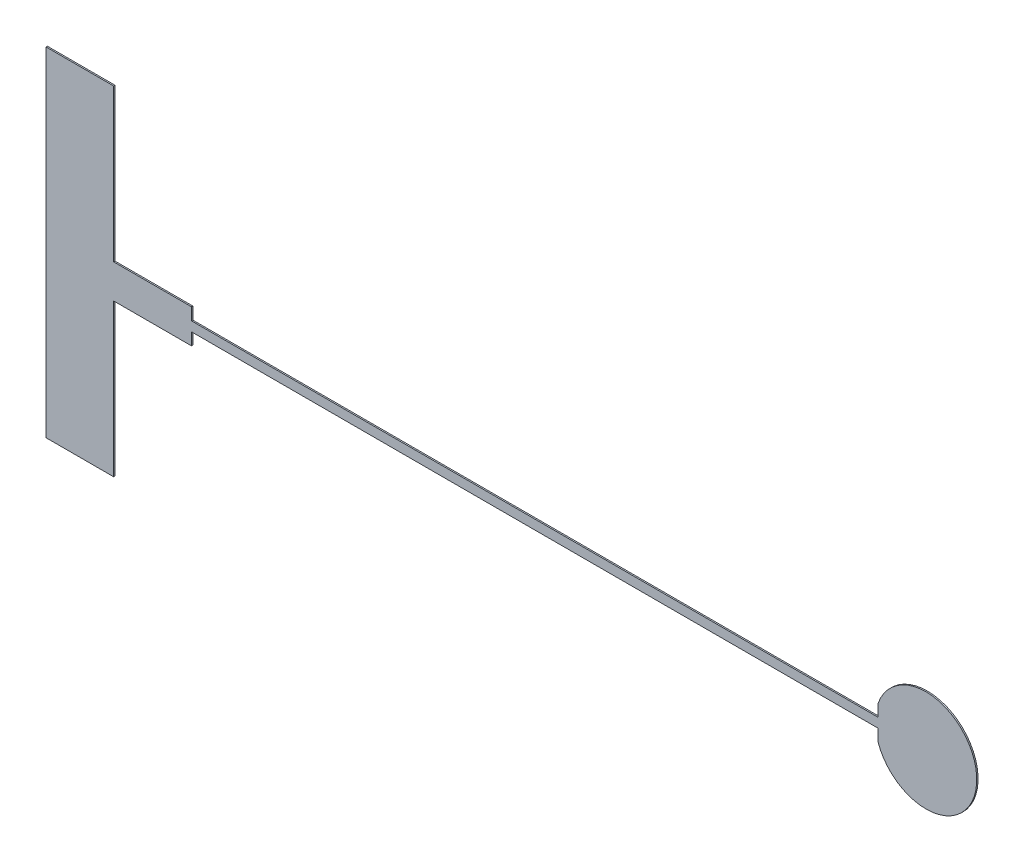
SolidWorks part; units mm, degrees
ref_plane "Front Plane" through (0, 0, 0) normal (0, 0, 1) x (1, 0, 0)
ref_plane "Top Plane" through (0, 0, 0) normal (0, 1, 0) x (1, 0, 0)
ref_plane "Right Plane" through (0, 0, 0) normal (1, 0, 0) x (0, 0, -1)
sketch "Sketch1" plane through (0, 0, 0) normal (0, 0, 1) x (1, 0, 0)
  line L0 (1000, 250) -> (5000, 250)
  line L1 (-1000, 2500) -> (1000, 2500)
  line L2 (-1000, 2500) -> (-1000, -2500)
  line L3 (-1000, -2500) -> (1000, -2500)
  line L4 (1000, 2500) -> (1000, 250)
  line L5 (-1000, 2500) -> (1000, -2500) construction
  line L6 (-1000, -2500) -> (1000, 2500) construction
  line L9 (1000, -250) -> (5000, -250)
  line L10 (5000, 250) -> (5000, 125)
  line L11 (-3000, 250) -> (5000, -250) construction
  line L12 (-3000, -250) -> (5000, 250) construction
  line L13 (5000, 125) -> (9000, 125)
  line L15 (5000, -125) -> (9000, -125)
  line L16 (9000, 125) -> (9000, 100)
  line L17 (1000, 125) -> (9000, -125) construction
  line L18 (1000, -125) -> (9000, 125) construction
  line L19 (9000, 100) -> (11256.6966, 100)
  line L21 (9000, -100) -> (11256.6966, -100)
  line L23 (6000, 100) -> (12000, -100) construction
  line L24 (6000, -100) -> (12000, 100) construction
  line L25 (1000, -250) -> (1000, -2500)
  line L26 (5000, -125) -> (5000, -250)
  line L27 (9000, -100) -> (9000, -125)
  arc A0 (11256.6966, -100) -> (11256.6966, 100) centre (12000, 0) ccw
  point P0 (0, 0)
  point P6 (1000, 0)
  point P11 (5000, 0)
  point P16 (9000, 0)
  dimension "D9" = 1500
  dimension "D1" = 2000
  dimension "D2" = 5000
  dimension "D3" = 500
  dimension "D4" = 4000
  dimension "D5" = 250
  dimension "D6" = 4000
  dimension "D7" = 200
extrude "Boss-Extrude1" add sketch "Sketch1" against normal blind 20
sketch "Sketch2" plane through (0, 0, 0) normal (0, 0, 1) x (1, 0, 0)
  line L0 (0, -11) -> (0, 11) construction
  line L1 (1000, 2500) -> (0, 2500)
  line L2 (1000, 2500) -> (1000, 250)
  line L3 (1000, 250) -> (0, 250)
  line L4 (0, 2500) -> (0, 250)
  line L5 (1000, -2500) -> (0, -2500)
  line L6 (1000, -2500) -> (1000, -250)
  line L7 (1000, -250) -> (0, -250)
  line L8 (0, -2500) -> (0, -250)
  dimension "D1" = 1000
  dimension "D2" = 2250
extrude "Cut-Extrude1" cut sketch "Sketch2" against normal through all
sketch "Sketch3" plane through (0, 0, 0) normal (0, 0, 1) x (1, 0, 0)
  line L0 (0, 0) -> (1098.3807, 0) construction
  line L1 (11, 0) -> (-11, 0) construction
  line L2 (5000, 250) -> (0, 250) construction
  line L3 (1500, 250) -> (3250, 250)
  line L4 (1500, 250) -> (1500, 200)
  line L5 (1500, 200) -> (3250, 200)
  line L7 (0, -250) -> (5000, -250) construction
  line L8 (1500, -250) -> (3250, -250)
  line L9 (1500, -250) -> (1500, -200)
  line L10 (1500, -200) -> (3250, -200)
  line L12 (0, -11) -> (0, 11) construction
  line L13 (3250, 200) -> (3250, 150)
  line L14 (3250, 250) -> (5000, 250)
  line L16 (3250, 150) -> (5000, 150)
  line L17 (5000, 250) -> (5000, 150)
  line L18 (3250, -250) -> (5000, -250)
  line L19 (3250, -200) -> (3250, -150)
  line L20 (3250, -150) -> (5000, -150)
  line L21 (5000, -250) -> (5000, -150)
  point P17 (1500, 225)
  dimension "D1" = 1098.3807
  dimension "D2" = 1750
  dimension "D3" = 50
  dimension "D4" = 1750
  dimension "D5" = 50
  dimension "D6" = 1500
  dimension "D7" = 1500
  dimension "D8" = 100
  dimension "D9" = 100
  dimension "D10" = 1750
  dimension "D11" = 1750
extrude "Cut-Extrude4" cut sketch "Sketch3" against normal through all contours L8 L18 L21 L20 L19 L10 L9
mirror "Mirror1" about plane through (0, 0, 0) normal (0, 1, 0) of "Cut-Extrude4"
sketch "Sketch5" plane through (0, 0, 0) normal (0, 0, 1) x (1, 0, 0)
  line L0 (0, -11) -> (0, 11) construction
  line L1 (0, -250) -> (11500, -250)
  line L2 (0, -250) -> (0, 250)
  line L3 (0, 250) -> (11500, 250)
  line L4 (11500, -250) -> (11500, 250)
  line L5 (0, -250) -> (1500, -250) construction
  dimension "D1" = 500
  dimension "D2" = 11500
extrude "Boss-Extrude2" add sketch "Sketch5" against normal blind 20
sketch "Sketch7" plane through (0, 0, 0) normal (0, 0, 1) x (1, 0, 0)
  line L0 (11292.8932, 250) -> (0, 250) construction
  line L1 (1150, 250) -> (11292.8932, 250)
  line L2 (1150, 250) -> (1150, 70)
  line L3 (1150, 70) -> (11292.8932, 70)
  line L4 (11292.8932, 250) -> (11292.8932, 70)
  line L5 (0, 2500) -> (0, 250) construction
  dimension "D1" = 1150
  dimension "D2" = 0
  dimension "D3" = 180
extrude "Cut-Extrude5" cut sketch "Sketch7" against normal through all
mirror "Mirror2" about plane through (0, 0, 0) normal (0, 1, 0) of "Cut-Extrude5"
